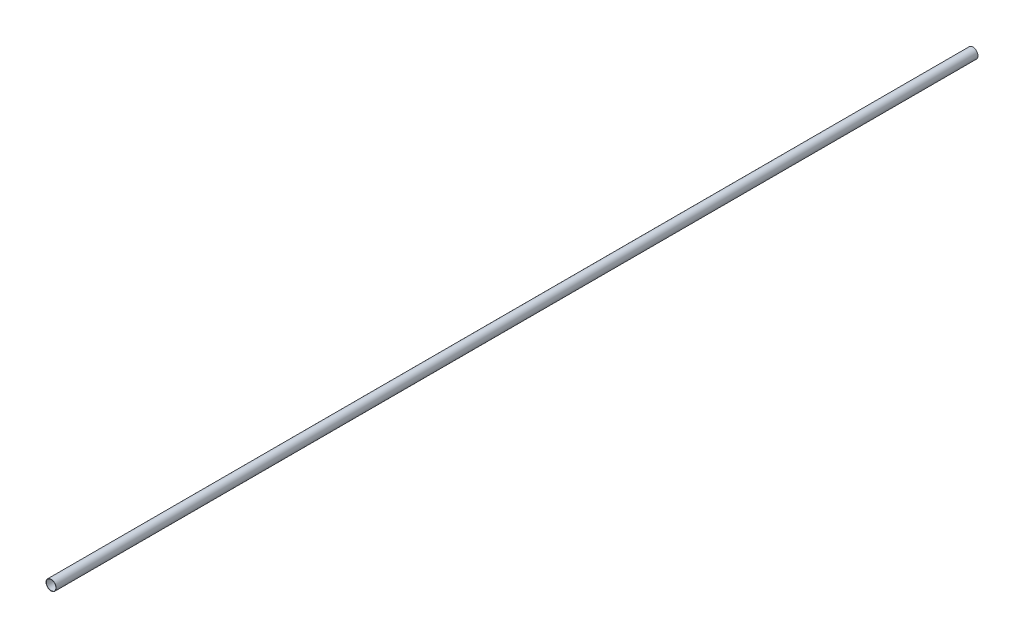
SolidWorks part; units mm, degrees
material "6061-T6 (SS)"
ref_plane "Front Plane" through (0, 0, 0) normal (0, 0, 1) x (1, 0, 0)
ref_plane "Top Plane" through (0, 0, 0) normal (0, 1, 0) x (1, 0, 0)
ref_plane "Right Plane" through (0, 0, 0) normal (1, 0, 0) x (0, 0, -1)
sketch "Sketch1" plane through (0, 0, 0) normal (0, 0, 1) x (1, 0, 0)
  circle A0 centre (-113.0054, -113.0054) radius 4.318
  circle A1 centre (-113.0054, -113.0054) radius 4.572
  dimension "D1" = 0.254
  dimension "D2" = 8.636
extrude "Boss-Extrude1" add sketch "Sketch1" along normal blind 825.5
